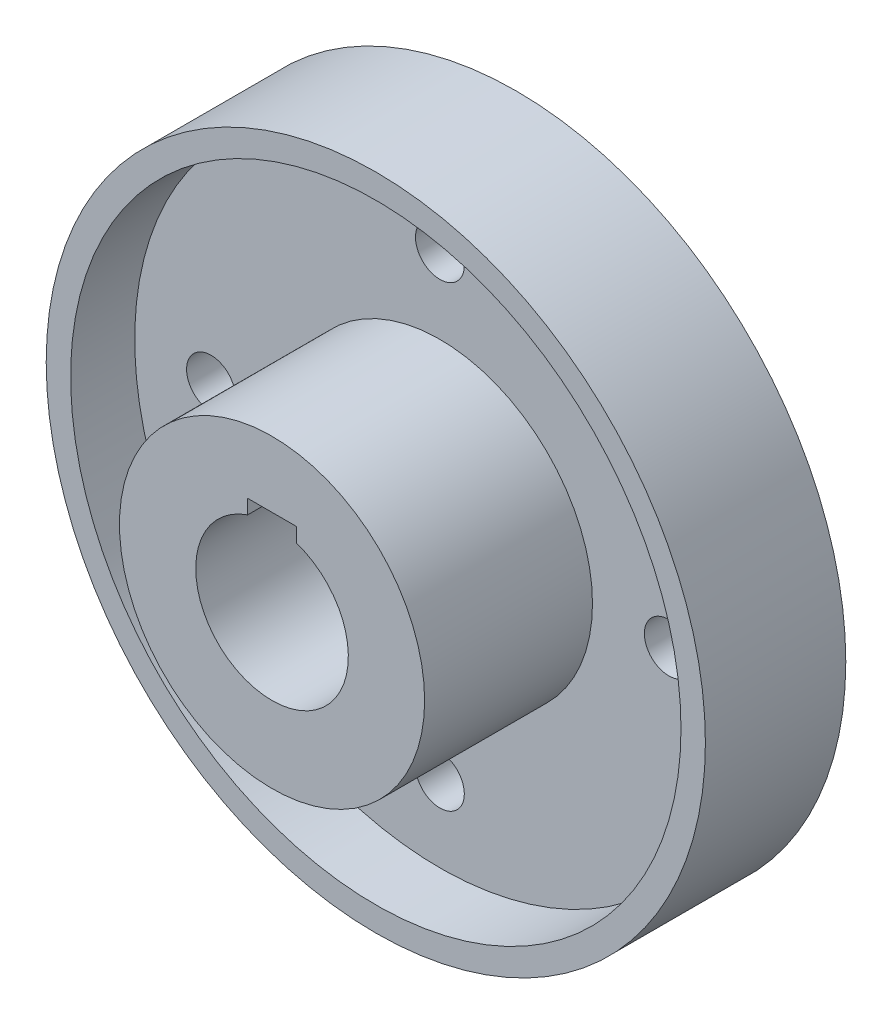
SolidWorks part; units mm, degrees
material "Stainless Steel (ferritic)"
ref_plane "Front Plane" through (0, 0, 0) normal (0, 0, 1) x (1, 0, 0)
ref_plane "Top Plane" through (0, 0, 0) normal (0, 1, 0) x (1, 0, 0)
ref_plane "Right Plane" through (0, 0, 0) normal (1, 0, 0) x (0, 0, -1)
sketch "Sketch1" plane through (0, 0, 0) normal (0, 0, 1) x (1, 0, 0)
  line L0 (0, 0) -> (-167.125, 0) construction
  line L1 (0, 15.995) -> (0, 50015.995) construction
  line L2 (-8, 28.4) -> (8, 28.4)
  line L3 (8, 28.4) -> (8, 23.6854)
  line L4 (-8, 28.4) -> (-8, 23.6854)
  circle A0 centre (0, 0) radius 50
  arc A1 (-8, 23.6854) -> (8, 23.6854) centre (0, 0) ccw
  point P4 (0, -25)
  point P11 (0, 28.4)
  dimension "D1" = 100
  dimension "D2" = 50
  dimension "D3" = 53.4
  dimension "D4" = 16
extrude "Boss-Extrude1" add sketch "Sketch1" along normal blind 80
sketch "Sketch2" plane through (0, 0, 0) normal (0, 0, -1) x (-1, 0, 0)
  circle A0 centre (0, 0) radius 50
  circle A1 centre (0, 0) radius 108
  circle A2 centre (0, 75) radius 8
  circle A3 centre (75, 0) radius 8
  circle A4 centre (0, -75) radius 8
  circle A5 centre (-75, 0) radius 8
  point P15 (0, 0)
  dimension "D1" = 100
  dimension "D2" = 216
  dimension "D4" = 16
  dimension "D3" = 75
  dimension "D5" = 4
extrude "Boss-Extrude3" add sketch "Sketch2" against normal blind 46
sketch "Sketch3" plane through (0, 0, 0) normal (0, 0, -1) x (-1, 0, 0)
  line L0 (-8, 23.6854) -> (-8, 28.4) construction
  line L1 (-8, 28.4) -> (8, 28.4) construction
  line L2 (8, 28.4) -> (8, 23.6854) construction
  line L3 (-8, 23.6854) -> (-8, 28.4)
  line L4 (-8, 28.4) -> (8, 28.4)
  line L5 (8, 28.4) -> (8, 23.6854)
  arc A0 (-8, 23.6854) -> (8, 23.6854) centre (0, 0) ccw construction
  arc A1 (-8, 23.6854) -> (8, 23.6854) centre (0, 0) ccw
  circle A2 centre (0, 0) radius 50
  dimension "D1" = 100
extrude "Boss-Extrude4" add sketch "Sketch3" along normal blind 5
chamfer "Chamfer1" distance 2 angle 45 1 edges at (-50, 0, -5)
sketch "Sketch6" plane through (0, 0, 46) normal (0, 0, 1) x (1, 0, 0)
  circle A0 centre (0, 0) radius 50 construction
  circle A1 centre (0, 0) radius 50
  circle A2 centre (0, 0) radius 100
  dimension "200" = 200
extrude "Cut-Extrude1" cut sketch "Sketch6" against normal blind 21
